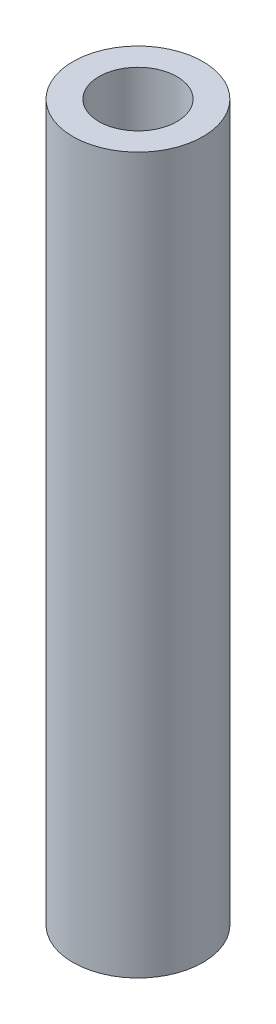
SolidWorks part; units mm, degrees
ref_plane "Front Plane" through (0, 0, 0) normal (0, 0, 1) x (1, 0, 0)
ref_plane "Top Plane" through (0, 0, 0) normal (0, 1, 0) x (1, 0, 0)
ref_plane "Right Plane" through (0, 0, 0) normal (1, 0, 0) x (0, 0, -1)
sketch "Sketch1" plane through (0, 0, 0) normal (0, 1, 0) x (1, 0, 0)
  circle A0 centre (0, 0) radius 5
  circle A1 centre (0, 0) radius 3
  dimension "D1" = 10
  dimension "D2" = 6
extrude "Boss-Extrude1" add sketch "Sketch1" along normal blind 55
